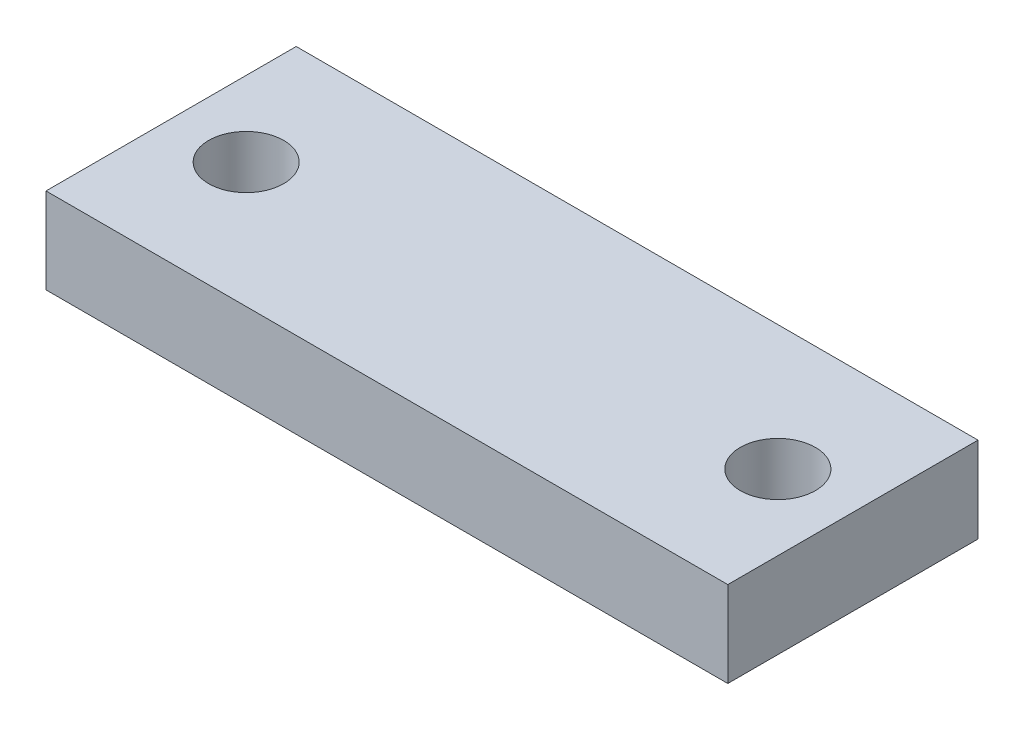
SolidWorks part; units mm, degrees
ref_plane "前视基准面" through (0, 0, 0) normal (0, 0, 1) x (1, 0, 0)
ref_plane "上视基准面" through (0, 0, 0) normal (0, 1, 0) x (1, 0, 0)
ref_plane "右视基准面" through (0, 0, 0) normal (1, 0, 0) x (0, 0, -1)
other "Configuration Table"
sketch "草图1" plane through (0, 0, 0) normal (0, 1, 0) x (1, 0, 0)
  line L0 (27.25, 0) -> (27.25, -20) construction
  line L1 (0, 0) -> (54.5, 0)
  line L2 (0, 0) -> (0, -20)
  line L3 (0, -20) -> (54.5, -20)
  line L4 (54.5, 0) -> (54.5, -20)
  circle A0 centre (48.5, -10) radius 3
  circle A1 centre (6, -10) radius 3
  dimension "D3" = 6
  dimension "D4" = 6
  dimension "D1" = 54.5
  dimension "D2" = 20
extrude "凸台-拉伸1" add sketch "草图1" along normal blind 6.85
